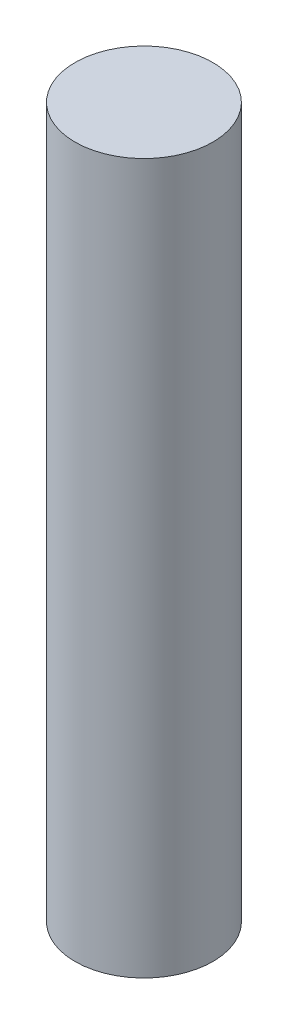
SolidWorks part; units mm, degrees
ref_plane "Front Plane" through (0, 0, 0) normal (0, 0, 1) x (1, 0, 0)
ref_plane "Top Plane" through (0, 0, 0) normal (0, 1, 0) x (1, 0, 0)
ref_plane "Right Plane" through (0, 0, 0) normal (1, 0, 0) x (0, 0, -1)
sketch "Sketch1" plane through (0, 0, 0) normal (0, 1, 0) x (1, 0, 0)
  circle A0 centre (0, 0) radius 4.318
  dimension "D1" = 8.636
extrude "Boss-Extrude1" add sketch "Sketch1" along normal blind 44.45 contours A0
